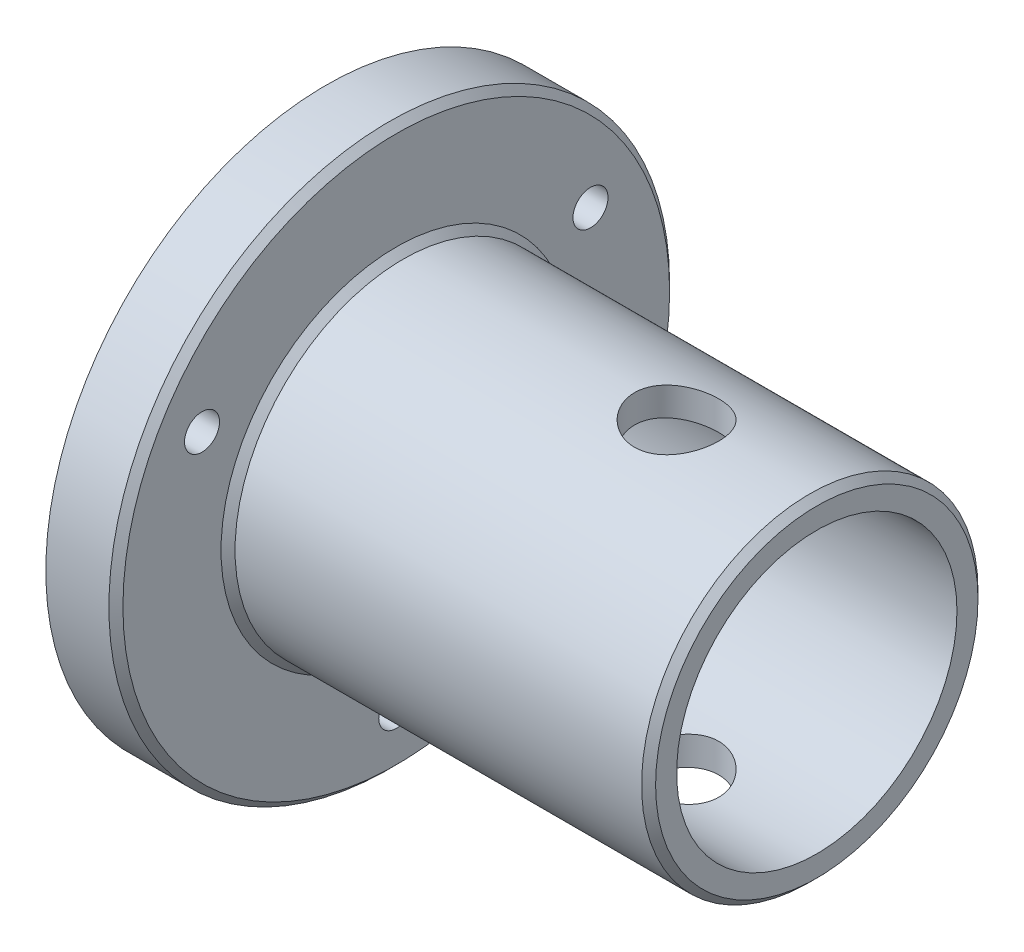
SolidWorks part; units mm, degrees
ref_plane "Front" through (0, 0, 0) normal (0, 0, 1) x (1, 0, 0)
ref_plane "Top" through (0, 0, 0) normal (0, 1, 0) x (1, 0, 0)
ref_plane "Right" through (0, 0, 0) normal (1, 0, 0) x (0, 0, -1)
sketch "草图1" plane through (0, 0, 0) normal (1, 0, 0) x (0, 0, -1)
  line L0 (0, 0) -> (0, -16) construction
  line L1 (0, 0) -> (13.8564, 8) construction
  line L2 (0, 0) -> (-13.8564, 8) construction
  circle A0 centre (0, 0) radius 10
  circle A1 centre (0, 0) radius 20
  circle A2 centre (0, 0) radius 16 construction
  circle A3 centre (0, 0) radius 12
extrude "凸台-拉伸1" add sketch "草图1" along normal blind 5 contours A1
hole_wizard "M3x0.5 螺纹孔1" positions "草图4" profile "草图5" tap size "M3x0.5" standard "ANSI Metric"
sketch "草图4" plane through (0, 0, 0) normal (-1, 0, 0) x (0, 0, 1)
  point P0 (-13.8564, 8)
  point P3 (13.8564, 8)
  point P6 (0, -16)
sketch "草图5" plane through (0, 8, -13.8564) normal (0, 1, 0) x (0, 0, 1)
  line L0 (0, 0) -> (0, 8.2511)
  line L1 (0, 8.2511) -> (1.25, 7.5)
  line L2 (1.25, 7.5) -> (1.25, 0)
  line L5 (1.25, 0) -> (0, 0)
  line L10 (0, 8.2511) -> (-1.25, 7.5) construction
  line L11 (0, -6.35) -> (0, 107.95) construction
  dimension "螺纹孔钻头直径" = 2.5
  dimension "螺纹孔钻头深度" = 7.5
  dimension "导头角度" = 118
cosmetic thread "孔螺蚊线1" parameters "D1"=6, "D2"=3
cosmetic thread "孔螺蚊线2" parameters "D1"=6, "D2"=3
cosmetic thread "孔螺蚊线3" parameters "D1"=6, "D2"=3
sketch "草图6" plane through (5, 0, 0) normal (1, 0, 0) x (0, 0, -1)
  circle A0 centre (0, 0) radius 10
  circle A1 centre (0, 0) radius 12
extrude "凸台-拉伸2" add sketch "草图6" along normal blind 30 contours A1
sketch "草图7" plane through (35, 0, 0) normal (1, 0, 0) x (0, 0, -1)
  circle A0 centre (0, 0) radius 10
extrude "切除-拉伸2" cut sketch "草图7" against normal blind 30
chamfer "倒角1" distance 0.5 angle 45 1 edges at (35, 0, -12)
sketch "草图8" plane through (0, 0, 0) normal (0, 1, 0) x (1, 0, 0)
  line L0 (5, 0) -> (25, 0) construction
  line L1 (5, -20) -> (5, 20) construction
  circle A0 centre (25, 0) radius 3
extrude "切除-拉伸3" cut sketch "草图8" along normal through all both and the other way through all
chamfer "倒角2" distance 0.5 angle 45 1 edges at (5, 0, -20)
chamfer "倒角3" distance 0.5 angle 45 1 edges at (5, 0, -12)
